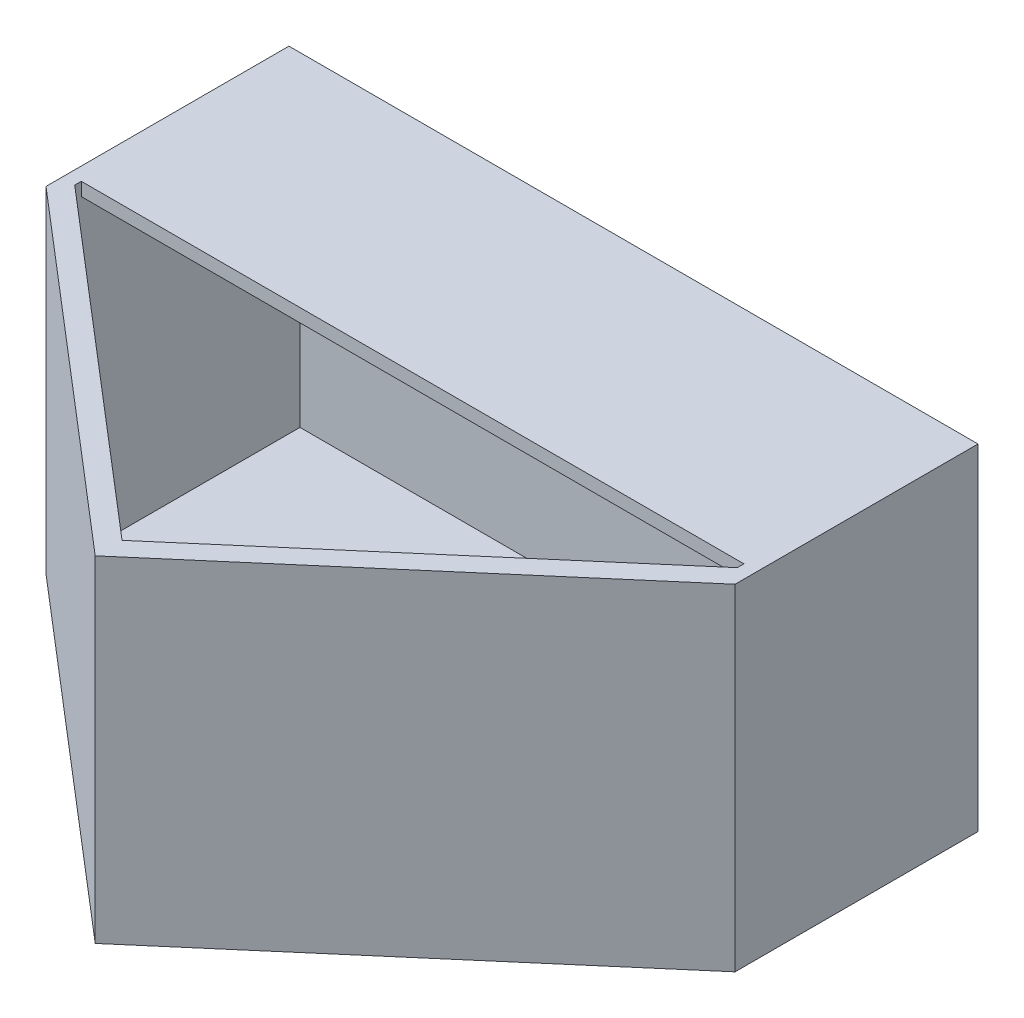
SolidWorks part; units mm, degrees
ref_plane "Front Plane" through (0, 0, 0) normal (0, 0, 1) x (1, 0, 0)
ref_plane "Top Plane" through (0, 0, 0) normal (0, 1, 0) x (1, 0, 0)
ref_plane "Right Plane" through (0, 0, 0) normal (1, 0, 0) x (0, 0, -1)
sketch "Sketch1" plane through (0, 0, 0) normal (0, 0, 1) x (1, 0, 0)
  line L1 (-691.7393, 433.0061) -> (808.2607, 433.0061)
  line L2 (-691.7393, 433.0061) -> (-691.7393, -266.9939)
  line L3 (-691.7393, -266.9939) -> (808.2607, -266.9939)
  line L4 (808.2607, 433.0061) -> (808.2607, -266.9939)
  line L5 (-721.7393, 463.0061) -> (838.2607, 463.0061)
  line L6 (-721.7393, 463.0061) -> (-721.7393, -296.9939)
  line L7 (-721.7393, -296.9939) -> (838.2607, -296.9939)
  line L8 (838.2607, 463.0061) -> (838.2607, -296.9939)
  dimension "D1" = 700
  dimension "D2" = 1500
  dimension "D3" = 30
  dimension "D4" = 30
  dimension "D5" = 30
  dimension "D6" = 30
extrude "Boss-Extrude1" add sketch "Sketch1" along normal blind 500
sketch "Sketch2" plane through (0, 0, 0) normal (0, 0, 1) x (1, 0, 0)
  line L1 (-691.7393, 433.0061) -> (808.2607, 433.0061)
  line L2 (-691.7393, 433.0061) -> (-691.7393, -266.9939)
  line L3 (-691.7393, -266.9939) -> (808.2607, -266.9939)
  line L4 (808.2607, 433.0061) -> (808.2607, -266.9939)
extrude "Boss-Extrude2" add sketch "Sketch2" along normal blind 5
sketch "Sketch5" plane through (0, 0, 500) normal (0, 0, 1) x (1, 0, 0)
  line L0 (838.2607, 463.0061) -> (-721.7393, 463.0061) construction
  line L1 (838.2607, -296.9939) -> (808.2607, -296.9939)
  line L2 (838.2607, -296.9939) -> (838.2607, 463.0061)
  line L3 (838.2607, 463.0061) -> (808.2607, 463.0061)
  line L4 (808.2607, -296.9939) -> (808.2607, 463.0061)
  dimension "D1" = 30
extrude "Boss-Extrude3" add sketch "Sketch5" along normal blind 50
sketch "Sketch6" plane through (0, 463.0061, 0) normal (0, 1, 0) x (1, 0, 0)
  line L0 (838.2607, -550) -> (808.2607, -515)
  line L1 (808.2607, -550) -> (808.2607, -500) construction
  line L2 (808.2607, -515) -> (808.2607, -550)
  line L3 (808.2607, -550) -> (838.2607, -550)
  dimension "D1" = 35
  dimension "D2" = 30
  dimension "D3" = 46.0977
extrude "Cut-Extrude1" cut sketch "Sketch6" against normal up to next
sketch "Sketch7" plane through (211.4679, 0, -181.2582) normal (-0.7593, 0, 0.6508) x (0.6508, 0, 0.7593)
  line L1 (963.124, 463.0061) -> (917.0262, 463.0061)
  line L2 (963.124, 463.0061) -> (963.124, -296.9939)
  line L3 (963.124, -296.9939) -> (917.0262, -296.9939)
  line L4 (917.0262, 463.0061) -> (917.0262, -296.9939)
extrude "Boss-Extrude4" add sketch "Sketch7" along normal blind 1709
sketch "Sketch8" plane through (0, 0, 500) normal (0, 0, 1) x (1, 0, 0)
  line L0 (808.2607, 463.0061) -> (-721.7393, 463.0061) construction
  line L1 (-721.7393, -296.9939) -> (-691.7393, -296.9939)
  line L2 (-721.7393, -296.9939) -> (-721.7393, 463.0061)
  line L3 (-721.7393, 463.0061) -> (-691.7393, 463.0061)
  line L4 (-691.7393, -296.9939) -> (-691.7393, 463.0061)
  dimension "D1" = 30
extrude "Boss-Extrude5" add sketch "Sketch8" along normal blind 50
sketch "Sketch10" plane through (0, 463.0061, 0) normal (0, 1, 0) x (1, 0, 0)
  line L0 (-691.7393, -550) -> (-691.7393, -515)
  line L1 (-691.7393, -550) -> (-691.7393, -500) construction
  line L2 (-691.7393, -515) -> (-721.7393, -550)
  line L3 (-721.7393, -550) -> (-691.7393, -550)
  dimension "D1" = 35
extrude "Cut-Extrude2" cut sketch "Sketch10" against normal up to next
sketch "Sketch11" plane through (-144.2968, 0, -123.6829) normal (0.7593, 0, 0.6508) x (0.6508, 0, -0.7593)
  line L1 (-887.2928, -296.9939) -> (-841.1951, -296.9939)
  line L2 (-887.2928, -296.9939) -> (-887.2928, 463.0061)
  line L3 (-887.2928, 463.0061) -> (-841.1951, 463.0061)
  line L4 (-841.1951, -296.9939) -> (-841.1951, 463.0061)
extrude "Boss-Extrude6" add sketch "Sketch11" along normal up to next
sketch "Sketch12" plane through (0, 463.0061, 0) normal (0, 1, 0) x (1, 0, 0)
  line L1 (55.5364, -1220.9066) -> (-459.3088, -1662.2025)
  line L2 (-459.3088, -1662.2025) -> (-489.3088, -1627.2025)
  line L3 (-489.3088, -1627.2025) -> (22.844, -1188.2143)
  line L4 (-459.3088, -1662.2025) -> (838.2607, -550) construction
  line L5 (22.844, -1188.2143) -> (55.5364, -1220.9066)
  point P3 (55.5364, -1220.9066)
extrude "Cut-Extrude4" cut sketch "Sketch12" against normal blind 1023
sketch "Sketch13" plane through (0, 463.0061, 0) normal (0, 1, 0) x (1, 0, 0)
  line L0 (22.844, -1188.2143) -> (58.2607, -1218.5714)
  line L1 (55.5364, -1220.9066) -> (838.2607, -550) construction
  line L2 (58.2607, -1218.5714) -> (55.5364, -1220.9066)
  line L3 (55.5364, -1220.9066) -> (22.844, -1188.2143)
extrude "Cut-Extrude5" cut sketch "Sketch13" against normal blind 1023
sketch "Sketch14" plane through (0, 0, 500) normal (0, 0, 1) x (1, 0, 0)
  line L1 (-691.7393, -296.9939) -> (808.2607, -296.9939)
  line L2 (-691.7393, -296.9939) -> (-691.7393, -266.9939)
  line L3 (-691.7393, -266.9939) -> (808.2607, -266.9939)
  line L4 (808.2607, -296.9939) -> (808.2607, -266.9939)
extrude "Boss-Extrude7" add sketch "Sketch14" along normal up to next
sketch "Sketch15" plane through (0, 0, 500) normal (0, 0, 1) x (1, 0, 0)
  line L1 (808.2607, 433.0061) -> (-691.7393, 433.0061)
  line L2 (808.2607, 433.0061) -> (808.2607, 463.0061)
  line L3 (808.2607, 463.0061) -> (-691.7393, 463.0061)
  line L4 (-691.7393, 433.0061) -> (-691.7393, 463.0061)
